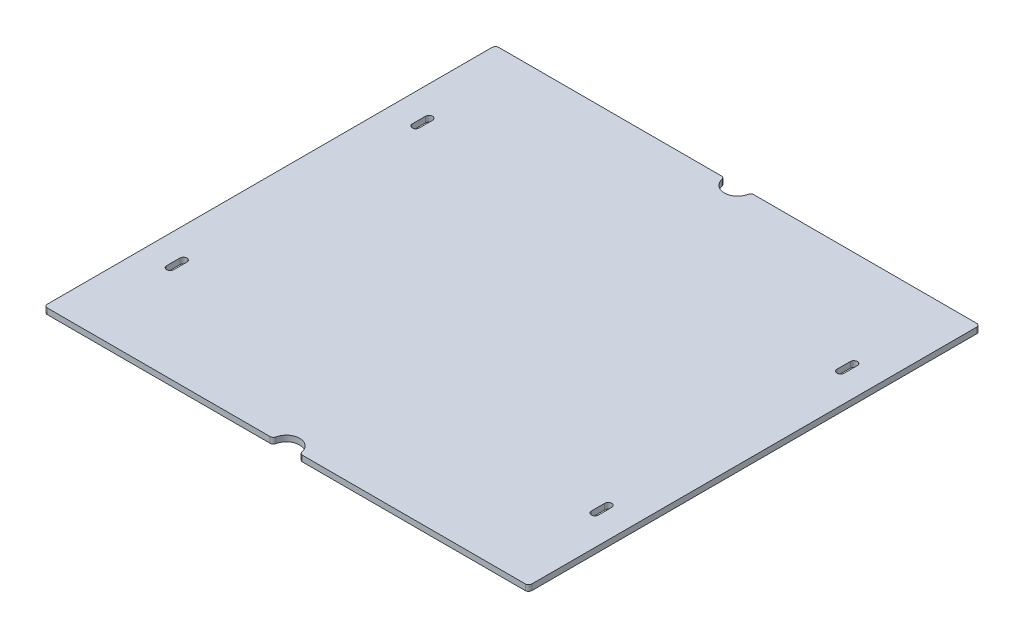
SolidWorks part; units mm, degrees
material "ABS PC"
ref_plane "Front Plane" through (0, 0, 0) normal (0, 0, 1) x (1, 0, 0)
ref_plane "Top Plane" through (0, 0, 0) normal (0, 1, 0) x (1, 0, 0)
ref_plane "Right Plane" through (0, 0, 0) normal (1, 0, 0) x (0, 0, -1)
sketch "Sketch1" plane through (0, 0, 0) normal (0, 1, 0) x (1, 0, 0)
  line L0 (28.575, 339.725) -> (28.575, 327.025) construction
  line L1 (0, 0) -> (463.55, 0)
  line L2 (0, 0) -> (0, 431.8)
  line L3 (0, 431.8) -> (463.55, 431.8)
  line L4 (463.55, 0) -> (463.55, 431.8)
  line L5 (31.9532, 339.725) -> (31.9532, 327.025)
  line L6 (25.1968, 339.725) -> (25.1968, 327.025)
  line L7 (0, 215.9) -> (463.55, 215.9) construction
  line L8 (28.575, 92.075) -> (28.575, 104.775) construction
  line L9 (31.9532, 92.075) -> (31.9532, 104.775)
  line L10 (25.1968, 92.075) -> (25.1968, 104.775)
  line L11 (231.775, 215.9) -> (231.775, 431.8) construction
  line L12 (434.975, 92.075) -> (434.975, 104.775) construction
  line L13 (431.5968, 92.075) -> (431.5968, 104.775)
  line L14 (438.3532, 92.075) -> (438.3532, 104.775)
  line L15 (434.975, 339.725) -> (434.975, 327.025) construction
  line L16 (431.5968, 339.725) -> (431.5968, 327.025)
  line L17 (438.3532, 339.725) -> (438.3532, 327.025)
  arc A0 (31.9532, 339.725) -> (25.1968, 339.725) centre (28.575, 339.725) ccw
  arc A1 (25.1968, 327.025) -> (31.9532, 327.025) centre (28.575, 327.025) ccw
  arc A2 (31.9532, 92.075) -> (25.1968, 92.075) centre (28.575, 92.075) cw
  arc A3 (25.1968, 104.775) -> (31.9532, 104.775) centre (28.575, 104.775) cw
  arc A4 (431.5968, 92.075) -> (438.3532, 92.075) centre (434.975, 92.075) ccw
  arc A5 (438.3532, 104.775) -> (431.5968, 104.775) centre (434.975, 104.775) ccw
  arc A6 (431.5968, 339.725) -> (438.3532, 339.725) centre (434.975, 339.725) cw
  arc A7 (438.3532, 327.025) -> (431.5968, 327.025) centre (434.975, 327.025) cw
  point P7 (28.575, 333.375)
  point P16 (28.575, 98.425)
  point P25 (434.975, 98.425)
  point P32 (434.975, 333.375)
  dimension "D3" = 6.7564
  dimension "D1" = 431.8
  dimension "D2" = 463.55
  dimension "D4" = 12.7
  dimension "D5" = 28.575
  dimension "D6" = 117.475
extrude "Boss-Extrude1" add sketch "Sketch1" along normal blind 5.588
fillet "Fillet1" radius 3.175 4 edges at (0, 2.794, -431.8) (463.55, 2.794, -431.8) (0, 2.794, 0) (463.55, 2.794, 0)
sketch "Sketch2" plane through (0, 5.588, 0) normal (0, 1, 0) x (1, 0, 0)
  line L0 (460.375, 431.8) -> (3.175, 431.8) construction
  line L1 (3.175, 0) -> (460.375, 0) construction
  circle A0 centre (231.775, 431.8) radius 12.7
  circle A1 centre (231.775, 0) radius 12.7
  dimension "D1" = 25.4
extrude "Cut-Extrude1" cut sketch "Sketch2" against normal through all
fillet "Fillet2" radius 3.175 4 edges at (219.075, 2.794, -431.8) (244.475, 2.794, -431.8) (244.475, 2.794, 0) (219.075, 2.794, 0)
